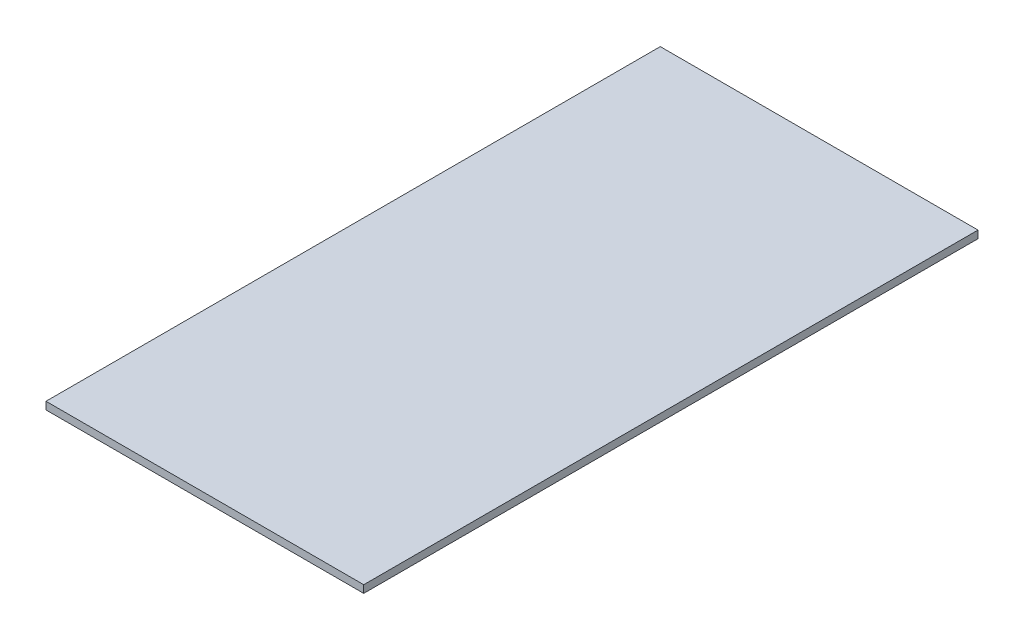
SolidWorks part; units mm, degrees
material "E-Glass Fiber"
ref_plane "Front Plane" through (0, 0, 0) normal (0, 0, 1) x (1, 0, 0)
ref_plane "Top Plane" through (0, 0, 0) normal (0, 1, 0) x (1, 0, 0)
ref_plane "Right Plane" through (0, 0, 0) normal (1, 0, 0) x (0, 0, -1)
sketch "Sketch1" plane through (0, 0, 0) normal (0, 1, 0) x (1, 0, 0)
  line L0 (0, -4.2398) -> (0, 81.0142) construction
  line L2 (0, -3.9116) -> (0, 3.9116) construction
  line L3 (-235.1361, 0) -> (-232.1568, 0) construction
  line L4 (-3.9116, 0) -> (3.9116, 0) construction
  line L5 (-150, 0) -> (-150, 580)
  line L6 (150, 0) -> (-150, 0)
  line L7 (150, 0) -> (150, 580)
  line L8 (150, 580) -> (-150, 580)
  point P13 (0, 0)
  dimension "D1" = 300
  dimension "D2" = 580
extrude "Boss-Extrude1" add sketch "Sketch1" along normal blind 7.112
